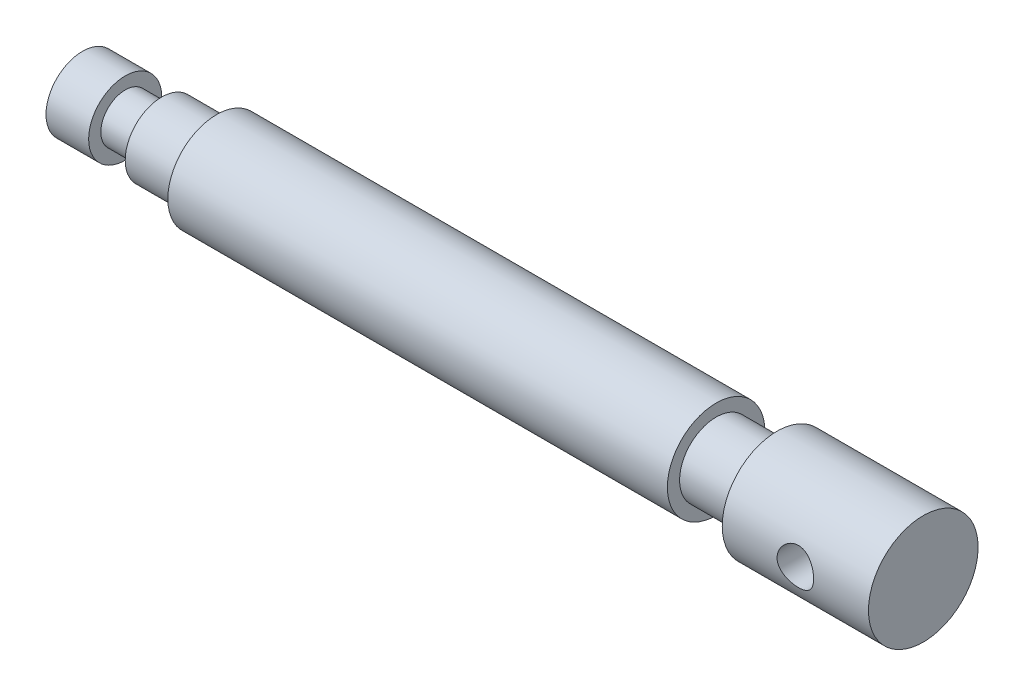
SolidWorks part; units mm, degrees
material "Alloy Steel"
ref_plane "Front Plane" through (0, 0, 0) normal (0, 0, 1) x (1, 0, 0)
ref_plane "Top Plane" through (0, 0, 0) normal (0, 1, 0) x (1, 0, 0)
ref_plane "Right Plane" through (0, 0, 0) normal (1, 0, 0) x (0, 0, -1)
sketch "Sketch1" plane through (0, 0, 0) normal (0, 0, 1) x (1, 0, 0)
  line L0 (0, 0) -> (138, 0) construction
  line L1 (0, 0) -> (0, 6)
  line L2 (0, 6) -> (7, 6)
  line L3 (7, 6) -> (7, 4)
  line L4 (7, 4) -> (13, 4)
  line L5 (13, 4) -> (13, 6)
  line L6 (13, 6) -> (22, 6)
  line L7 (22, 6) -> (22, 8)
  line L8 (22, 8) -> (104, 8)
  line L9 (104, 8) -> (104, 6)
  line L10 (104, 6) -> (114, 6)
  line L11 (114, 6) -> (114, 9)
  line L12 (114, 9) -> (138, 9)
  line L13 (138, 9) -> (138, 0)
  line L14 (0, 0) -> (138, 0)
  dimension "D1" = 138
  dimension "D2" = 24
  dimension "D3" = 10
  dimension "D4" = 82
  dimension "D5" = 7
  dimension "D6" = 6
  dimension "D7" = 4
  dimension "D8" = 6
  dimension "D9" = 8
  dimension "D10" = 9
revolve "Revolve1" add sketch "Sketch1" angle 360 about L0
sketch "Sketch2" plane through (0, 0, 0) normal (0, 0, 1) x (1, 0, 0)
  line L0 (138, 0) -> (114, 0) construction
  line L1 (138, -9) -> (138, 9) construction
  circle A0 centre (126, 0) radius 3
  dimension "D1" = 6
  dimension "D2" = 12
extrude "Cut-Extrude1" cut sketch "Sketch2" against normal mid plane 114
